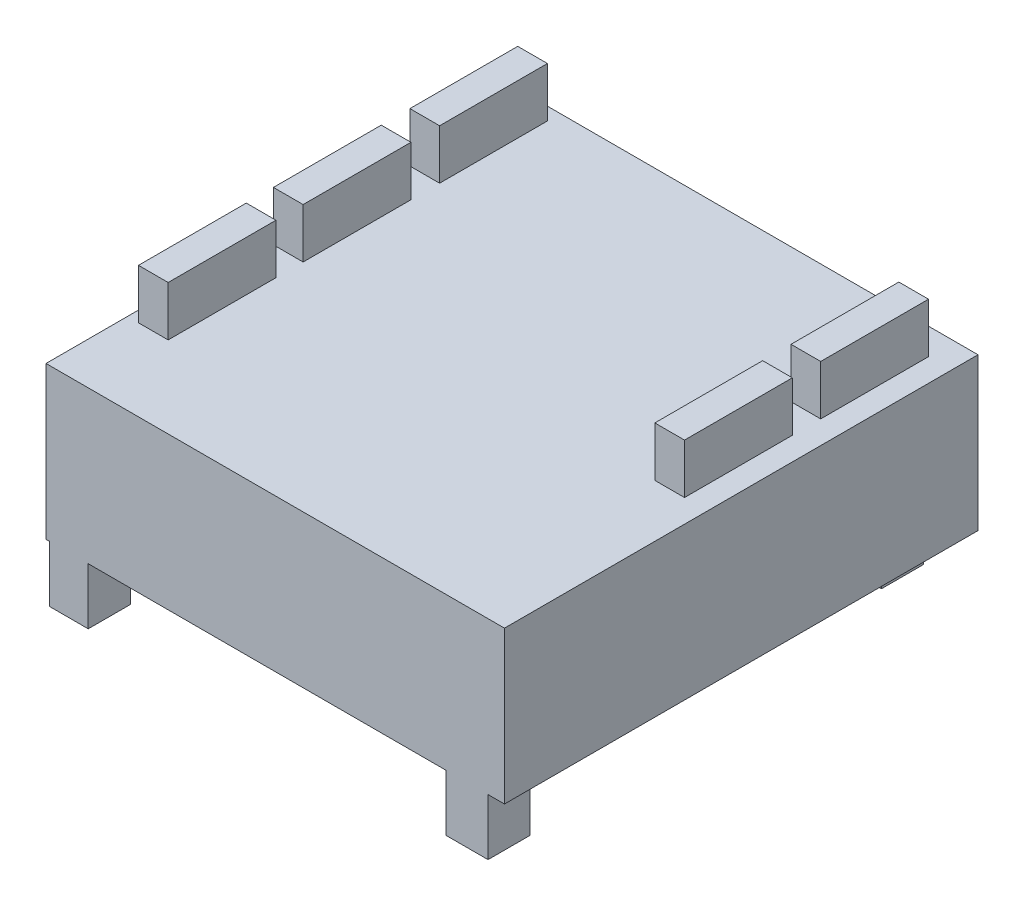
SolidWorks part; units mm, degrees
ref_plane "Front Plane" through (0, 0, 0) normal (0, 0, 1) x (1, 0, 0)
ref_plane "Top Plane" through (0, 0, 0) normal (0, 1, 0) x (1, 0, 0)
ref_plane "Right Plane" through (0, 0, 0) normal (1, 0, 0) x (0, 0, -1)
sketch "Sketch1" plane through (0, 0, 0) normal (0, 1, 0) x (1, 0, 0)
  line L1 (0, 0) -> (77.216, 0)
  line L2 (0, 0) -> (0, 79.756)
  line L3 (0, 79.756) -> (77.216, 79.756)
  line L4 (77.216, 0) -> (77.216, 79.756)
  dimension "D1" = 77.216
  dimension "D2" = 79.756
extrude "Base" add sketch "Sketch1" along normal blind 25.654
sketch "Sketch2" plane through (0, 25.654, 0) normal (0, 1, 0) x (1, 0, 0)
  line L0 (6.858, 59.436) -> (6.858, 54.61) construction
  line L1 (1.8542, 77.597) -> (6.858, 77.597)
  line L2 (1.8542, 77.597) -> (1.8542, 59.436)
  line L3 (1.8542, 59.436) -> (6.858, 59.436)
  line L4 (6.858, 77.597) -> (6.858, 59.436)
  line L5 (1.8542, 54.61) -> (6.858, 54.61)
  line L6 (1.8542, 54.61) -> (1.8542, 36.449)
  line L7 (1.8542, 36.449) -> (6.858, 36.449)
  line L8 (6.858, 54.61) -> (6.858, 36.449)
  line L9 (1.8542, 31.877) -> (6.858, 31.877)
  line L10 (1.8542, 31.877) -> (1.8542, 13.716)
  line L11 (1.8542, 13.716) -> (6.858, 13.716)
  line L12 (6.858, 31.877) -> (6.858, 13.716)
  line L13 (6.858, 36.449) -> (6.858, 31.877) construction
  line L14 (6.858, 77.597) -> (6.858, 79.756) construction
  line L15 (77.216, 79.756) -> (0, 79.756) construction
  line L16 (0, 79.756) -> (0, 0) construction
  line L17 (68.326, 57.15) -> (68.326, 52.3748) construction
  line L18 (68.326, 75.311) -> (73.3298, 75.311)
  line L19 (68.326, 75.311) -> (68.326, 57.15)
  line L20 (68.326, 57.15) -> (73.3298, 57.15)
  line L21 (73.3298, 75.311) -> (73.3298, 57.15)
  line L22 (68.326, 52.3748) -> (73.3298, 52.3748)
  line L23 (68.326, 52.3748) -> (68.326, 34.2138)
  line L24 (68.326, 34.2138) -> (73.3298, 34.2138)
  line L25 (73.3298, 52.3748) -> (73.3298, 34.2138)
  line L26 (68.326, 75.311) -> (68.326, 79.756) construction
  line L27 (77.216, 0) -> (77.216, 79.756) construction
  dimension "D1" = 18.161
  dimension "D2" = 4.826
  dimension "D3" = 4.572
  dimension "D4" = 6.858
  dimension "D5" = 5.0038
  dimension "D6" = 20.32
  dimension "D7" = 22.606
  dimension "D8" = 4.7752
  dimension "D9" = 8.89
extrude "Top Headers" add sketch "Sketch2" along normal blind 8.382
sketch "Sketch3" plane through (0, 0, 0) normal (0, -1, 0) x (1, 0, 0)
  line L0 (77.216, -79.756) -> (0, -79.756) construction
  line L1 (60.96, -79.756) -> (68.072, -79.756)
  line L2 (60.96, -79.756) -> (60.96, -72.644)
  line L3 (60.96, -72.644) -> (68.072, -72.644)
  line L4 (68.072, -79.756) -> (68.072, -72.644)
  line L5 (0, 0) -> (77.216, 0) construction
  line L6 (6.096, -79.756) -> (13.208, -79.756)
  line L7 (6.096, -79.756) -> (6.096, -72.644)
  line L8 (6.096, -72.644) -> (13.208, -72.644)
  line L9 (13.208, -79.756) -> (13.208, -72.644)
  line L10 (7.112, 0) -> (0.5842, 0)
  line L11 (7.112, 0) -> (7.112, -7.112)
  line L12 (7.112, -7.112) -> (0.5842, -7.112)
  line L13 (0.5842, 0) -> (0.5842, -7.112)
  line L14 (0, -79.756) -> (0, 0) construction
  line L15 (74.4474, 0) -> (67.3354, 0)
  line L16 (74.4474, 0) -> (74.4474, -7.112)
  line L17 (74.4474, -7.112) -> (67.3354, -7.112)
  line L18 (67.3354, 0) -> (67.3354, -7.112)
  line L19 (77.216, 0) -> (77.216, -79.756) construction
  dimension "D1" = 7.112
  dimension "D2" = 6.5278
  dimension "D3" = 7.112
  dimension "D4" = 7.112
  dimension "D5" = 9.8806
  dimension "D6" = 7.112
  dimension "D7" = 7.112
  dimension "D8" = 16.256
  dimension "D9" = 13.208
extrude "Boss-Extrude3" add sketch "Sketch3" along normal blind 9.4996
